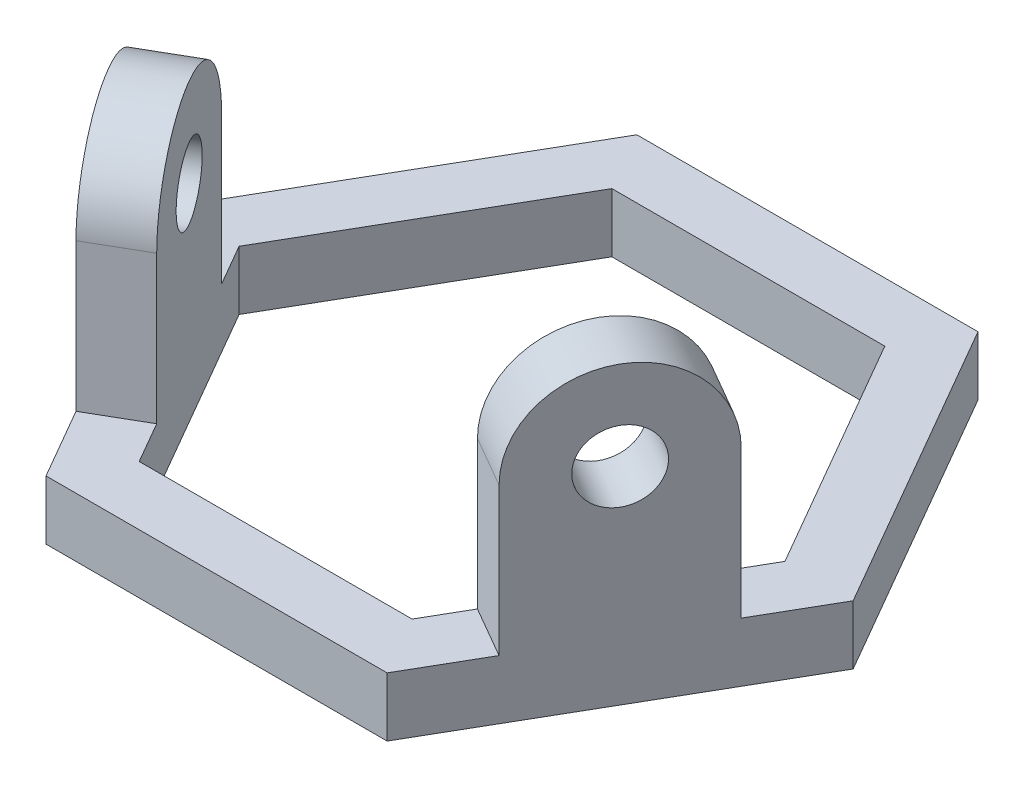
SolidWorks part; units mm, degrees
ref_plane "Front Plane" through (0, 0, 0) normal (0, 0, 1) x (1, 0, 0)
ref_plane "Top Plane" through (0, 0, 0) normal (0, 1, 0) x (1, 0, 0)
ref_plane "Right Plane" through (0, 0, 0) normal (1, 0, 0) x (0, 0, -1)
sketch "Sketch1" plane through (0, 0, 0) normal (0, 1, 0) x (1, 0, 0)
  line L0 (-55, 0) -> (55, 0) construction
  line L1 (57.735, 0) -> (28.8675, 50)
  line L2 (28.8675, 50) -> (-28.8675, 50)
  line L3 (-28.8675, 50) -> (-57.735, 0)
  line L4 (-57.735, 0) -> (-28.8675, -50)
  line L5 (-28.8675, -50) -> (28.8675, -50)
  line L6 (28.8675, -50) -> (57.735, 0)
  line L7 (46.188, 0) -> (23.094, 40)
  line L8 (23.094, 40) -> (-23.094, 40)
  line L9 (-23.094, 40) -> (-46.188, 0)
  line L10 (-46.188, 0) -> (-23.094, -40)
  line L11 (-23.094, -40) -> (23.094, -40)
  line L12 (23.094, -40) -> (46.188, 0)
  circle A0 centre (0, 0) radius 50 construction
  point P1 (0, 0)
  dimension "D1" = 100
  dimension "D2" = 10
extrude "Boss-Extrude1" add sketch "Sketch1" along normal blind 10
sketch "Sketch3" plane through (43.3013, 0, 25) normal (0.866, 0, 0.5) x (0.5, 0, -0.866)
  line L0 (-28.8675, 10) -> (28.8675, 10) construction
  line L1 (-15, 10) -> (-15, 35)
  line L2 (15, 35) -> (15, 10)
  line L3 (-15, 10) -> (15, 10)
  arc A0 (-15, 35) -> (15, 35) centre (0, 35) cw
  circle A1 centre (0, 35) radius 6
  point P0 (-28.8675, 10)
  point P1 (28.8675, 10)
  point P3 (0, 10)
  dimension "D1" = 15
  dimension "D3" = 12
  dimension "D2" = 35
extrude "Boss-Extrude2" add sketch "Sketch3" against normal blind 10
mirror "Mirror1" about plane through (0, 0, 0) normal (1, 0, 0) of "Boss-Extrude2"
